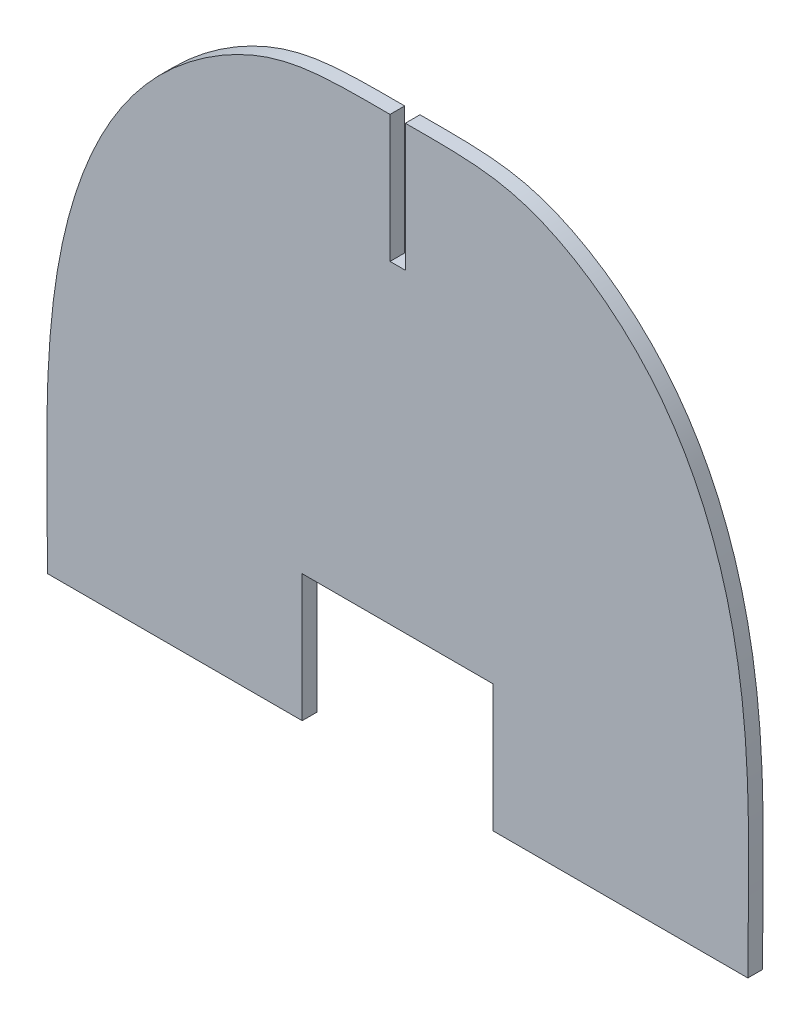
SolidWorks part; units mm, degrees
ref_plane "Front" through (0, 0, 0) normal (0, 0, 1) x (1, 0, 0)
ref_plane "Top" through (0, 0, 0) normal (0, 1, 0) x (1, 0, 0)
ref_plane "Right" through (0, 0, 0) normal (1, 0, 0) x (0, 0, -1)
sketch "Sketch1" plane through (0, 0, 0) normal (0, 0, 1) x (1, 0, 0)
  line L0 (139.7, 39.6875) -> (139.7, 143.4968) construction
  line L1 (0, 266.7) -> (89.6334, 266.7) construction
  spline S0 degree 3 poles (0, 266.7) (21.2133, 266.7) (50.2468, 267.6165) (111.1858, 228.5937) (143.5979, 144.6217) (139.7, 75.2223) (139.7, 39.6875) knots 0 0 0 0 0.165367 0.333681 0.645928 1 1 1 1
sketch "Sketch2" plane through (0, 0, 0) normal (0, 0, 1) x (1, 0, 0)
  line L0 (139.7, 39.6875) -> (0, 39.6875)
  line L1 (0, 39.6875) -> (0, 266.7)
  spline S0 degree 3 poles (-3581.8403, 2022.9991) (-144.6576, 28.0995) (-54.3162, 334.5743) (111.1858, 228.5937) (240.2909, -105.8875) (-305.1855, -476.4198) (4090.9669, 188.2398) knots -1.108323 -1.108323 -1.108323 -1.108323 0.165367 0.333681 0.645928 3.489916 3.489916 3.489916 3.489916 only from (0, 266.7) to (139.7, 39.6875) construction
  spline S1 degree 3 poles (0, 266.7) (21.2133, 266.7) (50.2468, 267.6165) (111.1858, 228.5937) (143.5979, 144.6217) (139.7, 75.2223) (139.7, 39.6875) knots 0 0 0 0 0.165367 0.333681 0.645928 1 1 1 1
extrude "Boss-Extrude1" add sketch "Sketch2" along normal blind 5.842
sketch "Sketch3" plane through (0, 0, 5.842) normal (0, 0, 1) x (1, 0, 0)
  line L0 (0, 266.7) -> (0, 268.8669)
  line L1 (0, 39.6875) -> (38.1, 39.6875)
  line L2 (0, 39.6875) -> (0, 90.4875)
  line L3 (0, 90.4875) -> (38.1, 90.4875)
  line L4 (38.1, 39.6875) -> (38.1, 90.4875)
  line L5 (0, 268.8669) -> (3.048, 268.8669)
  line L6 (0, 266.7) -> (0, 215.9)
  line L7 (0, 215.9) -> (3.048, 215.9)
  line L8 (3.048, 268.8669) -> (3.048, 215.9)
  dimension "D1" = 38.1
  dimension "D2" = 50.8
  dimension "D3" = 50.8
  dimension "D4" = 3.048
extrude "Cut-Extrude1" cut sketch "Sketch3" against normal through all
mirror "Mirror1" about plane through (0, 0, 0) normal (1, 0, 0) of bodies 102
